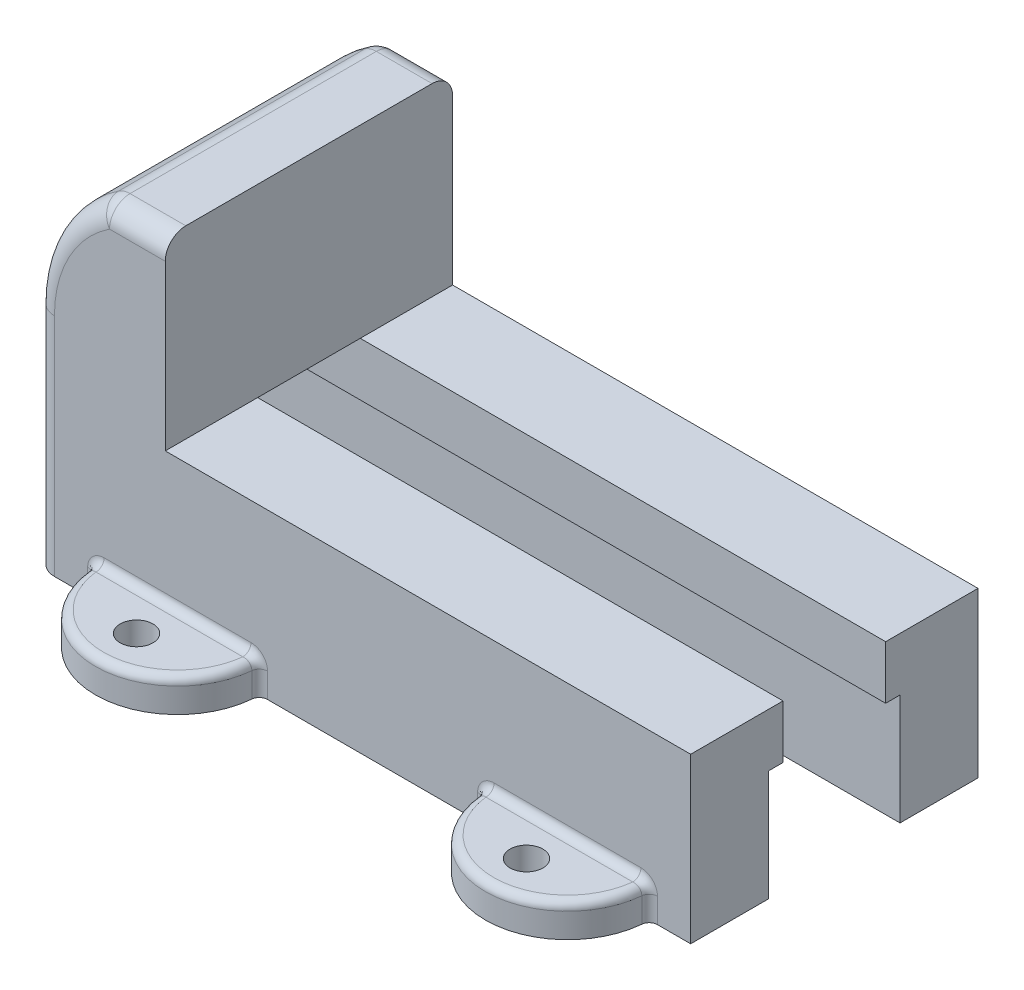
SolidWorks part; units mm, degrees
ref_plane "Front Plane" through (0, 0, 0) normal (0, 0, 1) x (1, 0, 0)
ref_plane "Top Plane" through (0, 0, 0) normal (0, 1, 0) x (1, 0, 0)
ref_plane "Right Plane" through (0, 0, 0) normal (1, 0, 0) x (0, 0, -1)
sketch "Sketch1" plane through (0, 0, 0) normal (0, 0, 1) x (1, 0, 0)
  line L1 (0, 0) -> (185, 0)
  line L2 (0, 0) -> (0, 40)
  line L3 (0, 40) -> (185, 40)
  line L4 (185, 0) -> (185, 40)
  dimension "D1" = 40
  dimension "D2" = 185
extrude "Extrude1" add sketch "Sketch1" along normal mid plane 70
sketch "Sketch2" plane through (0, 0, 35) normal (0, 0, 1) x (1, 0, 0)
  line L1 (0, 40) -> (32, 40)
  line L2 (0, 40) -> (0, 55)
  line L3 (16.9722, 85) -> (32, 85)
  line L4 (32, 40) -> (32, 85)
  arc A0 (0, 55) -> (16.9722, 85) centre (35, 55) cw
  dimension "D2" = 35
  dimension "D1" = 32
  dimension "D3" = 45
  dimension "D4" = 30
extrude "Extrude2" add sketch "Sketch2" against normal up to vertex (70 mm away) up to point (185, 40, -35)
sketch "Sketch3" plane through (185, 0, 0) normal (1, 0, 0) x (0, 0, -1)
  line L0 (-35, 0) -> (-35, 40) construction
  line L1 (-35, 40) -> (35, 40)
  line L2 (-35, 40) -> (-35, 55)
  line L3 (-35, 55) -> (-17, 55)
  line L4 (35, 40) -> (35, 55)
  line L5 (-35, 40) -> (35, 40) construction
  line L6 (-35, 0) -> (35, 0) construction
  line L7 (17, 55) -> (35, 55)
  line L8 (0, 50) -> (0, -50) construction
  arc A0 (17, 55) -> (-17, 55) centre (0, 55) ccw
  dimension "D2" = 17
  dimension "D1" = 55
extrude "Extrude3" add sketch "Sketch3" against normal blind 25
sketch "Sketch4" plane through (185, 0, 0) normal (1, 0, 0) x (0, 0, -1)
  line L0 (-35, 0) -> (35, 0) construction
  line L1 (-16, 0) -> (16, 0)
  line L2 (-12.5, 27) -> (-12.5, 40)
  line L3 (-12.5, 40) -> (12.5, 40)
  line L4 (12.5, 27) -> (12.5, 40)
  line L5 (-16, 0) -> (-16, 27)
  line L6 (-16, 27) -> (-12.5, 27)
  line L7 (16, 27) -> (16, 0)
  line L8 (0, 0) -> (0, 40) construction
  line L9 (12.5, 27) -> (16, 27)
  dimension "D1" = 40
  dimension "D2" = 25
  dimension "D3" = 32
  dimension "D4" = 27
extrude "Cut-Extrude1" cut sketch "Sketch4" against normal through all
sketch "Sketch5" plane through (0, 0, 0) normal (0, -1, 0) x (1, 0, 0)
  line L0 (0, 35) -> (185, 35) construction
  line L1 (15, 35) -> (55, 35)
  arc A0 (15, 35) -> (55, 35) centre (35, 35) cw
  dimension "D1" = 20
  dimension "D2" = 35
extrude "Extrude4" add sketch "Sketch5" against normal blind 8
sketch "Sketch6" plane through (0, 0, 0) normal (0, -1, 0) x (1, 0, 0)
  line L0 (55, 35) -> (185, 35) construction
  line L1 (110, 35) -> (150, 35)
  line L3 (185, 35) -> (185, 16) construction
  arc A0 (110, 35) -> (150, 35) centre (130, 35) cw
  dimension "D1" = 20
  dimension "D2" = 55
extrude "Extrude5" add sketch "Sketch6" against normal up to surface (8 mm away) up to face at (35, 8, 45)
mirror "Mirror1" about plane through (0, 0, 0) normal (0, 0, 1) of "Extrude5", "Extrude4"
hole_wizard "Ø8.0 (8) Diameter Hole1" positions "Sketch11" profile "Sketch10" hole size "Ø8.0" standard "Ansi Metric" end condition through all
sketch "Sketch11" plane through (0, 8, 0) normal (0, 1, 0) x (-1, 0, 0)
  line L0 (0, 0) -> (-84.8783, 0) construction
  line L2 (-35, 45) -> (-35, 35) construction
  line L3 (-130, 45) -> (-130, 35) construction
  line L11 (-15, 35) -> (-55, 35) construction
  point P0 (-35, 45)
  point P1 (-130, 45)
  point P35 (-35, -45)
  point P36 (-130, -45)
  dimension "D1" = 10
sketch "Sketch10" plane through (35, 8, 45) normal (1, 0, 0) x (0, 0, 1)
  line L0 (0, 0) -> (0, 8)
  line L1 (0, 8) -> (4, 8)
  line L2 (4, 8) -> (4, 0)
  line L5 (4, 0) -> (0, 0)
  line L11 (0, -6.35) -> (0, 107.95) construction
  dimension "Thru Hole Dia." = 8
  dimension "Thru Hole Depth" = 8
hole_wizard "Ø14.0 (14) Diameter Hole1" positions "Sketch8" profile "Sketch9" hole size "Ø14.0" standard "Ansi Metric"
sketch "Sketch8" plane through (185, 0, 0) normal (1, 0, 0) x (0, 0, -1)
  point P0 (0, 55)
sketch "Sketch9" plane through (185, 55, 0) normal (0, 1, 0) x (0, 0, -1)
  line L0 (0, 0) -> (0, 25)
  line L1 (0, 25) -> (7, 25)
  line L2 (7, 25) -> (7, 0)
  line L5 (7, 0) -> (0, 0)
  line L11 (0, -6.35) -> (0, 107.95) construction
  dimension "Thru Hole Dia." = 14
  dimension "Thru Hole Depth" = 25
fillet "Fillet1" radius 2 4 edges at (130, 8, -55) (35, 8, -55) (130, 8, 55) (35, 8, 55)
fillet "Fillet2" radius 2 24 edges at (15, 3, -35) (55, 3, -35) (54.4142, 7.4142, -35) (15.5858, 7.4142, -35) (110, 3, -35) (150, 3, -35) (149.4142, 7.4142, -35) (110.5858, 7.4142, -35) (150, 3, 35) (110, 3, 35) (149.4142, 7.4142, 35) (110.5858, 7.4142, 35) (55, 3, 35) (15, 3, 35) (54.4142, 7.4142, 35) (15.5858, 7.4142, 35) (172.5, 55, 35) (172.5, 55, -35) (172.5, 55, -17) (172.5, 55, 17) (35, 8, -35) (130, 8, -35) (130, 8, 35) (35, 8, 35)
fillet "Fillet3" radius 2 9 edges at (185, 26.5, -35) (185, 54.4142, -34.4142) (185, 55, -25.9472) (185, 55.5132, -17.5567) (185, 72, 0) (185, 55.5132, 17.5567) (185, 26.5, 35) (185, 54.4142, 34.4142) (185, 55, 25.9472)
fillet "Fillet10" radius 5 7 edges at (4.5371, 72.2341, 35) (4.5371, 72.2341, -35) (0, 27.5, 35) (0, 27.5, -35) (24.4861, 85, 35) (24.4861, 85, -35) (16.9722, 85, 0)
sketch "Sketch12" plane through (0, 0, 35) normal (0, 0, 1) x (1, 0, 0)
  line L0 (160, 86.7771) -> (160, -16.6768)
extrude "Cut-Extrude2" cut sketch "Sketch12" against normal through all and the other way through all
